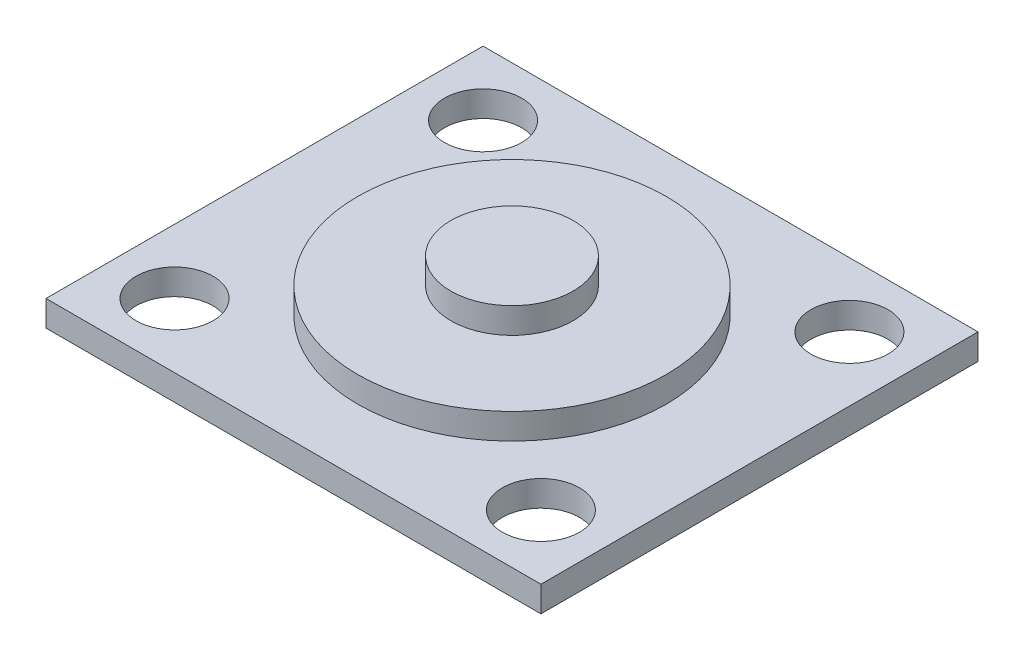
SolidWorks part; units mm, degrees
ref_plane "前视基准面" through (0, 0, 0) normal (0, 0, 1) x (1, 0, 0)
ref_plane "上视基准面" through (0, 0, 0) normal (0, 1, 0) x (1, 0, 0)
ref_plane "右视基准面" through (0, 0, 0) normal (1, 0, 0) x (0, 0, -1)
sketch "草图2" plane through (0, 0, 0) normal (0, 1, 0) x (1, 0, 0)
  line L0 (-24.2999, -37.6384) -> (4.2001, -37.6384)
  line L1 (4.2001, -37.6384) -> (4.2001, -13.6384)
  point P3 (0, 0)
sketch "草图3" plane through (0, 0, 0) normal (0, 1, 0) x (1, 0, 0)
  line L0 (-24.2999, -37.6384) -> (-24.2999, -13.6384)
  line L1 (-24.2999, -13.6384) -> (4.2001, -13.6384)
  line L2 (-29.2999, -8.6384) -> (9.2001, -8.6384)
  line L3 (9.2001, -42.6384) -> (9.2001, -8.6384)
  line L4 (-29.2999, -8.6384) -> (-29.2999, -42.6384)
  line L5 (-29.2999, -42.6384) -> (9.2001, -42.6384)
  circle A0 centre (-24.2999, -13.6384) radius 3
  circle A1 centre (4.2001, -13.6384) radius 3
  circle A2 centre (-24.2999, -37.6384) radius 3
  circle A3 centre (4.2001, -37.6384) radius 3
extrude "凸台-拉伸1" add sketch "草图3" along normal blind 2
sketch "草图4" plane through (0, 0, 0) normal (0, 1, 0) x (1, 0, 0)
  line L0 (-29.2999, -8.6384) -> (9.2001, -8.6384) construction
  line L1 (9.2001, -42.6384) -> (9.2001, -8.6384) construction
  circle A0 centre (-10.0499, -25.6384) radius 12
  point P4 (-10.0499, -8.6384)
  point P7 (9.2001, -25.6384)
extrude "凸台-拉伸3" add sketch "草图4" along normal blind 4 contours A0
sketch "草图6" plane through (0, 0, 0) normal (0, 1, 0) x (1, 0, 0)
  line L0 (-29.2999, -8.6384) -> (-29.2999, -42.6384) construction
  line L1 (-29.2999, -42.6384) -> (9.2001, -42.6384) construction
  circle A0 centre (-10.0499, -25.6384) radius 4.7581
  point P4 (-29.2999, -25.6384)
  point P7 (-10.0499, -42.6384)
extrude "凸台-拉伸4" add sketch "草图6" along normal blind 6 contours A0
